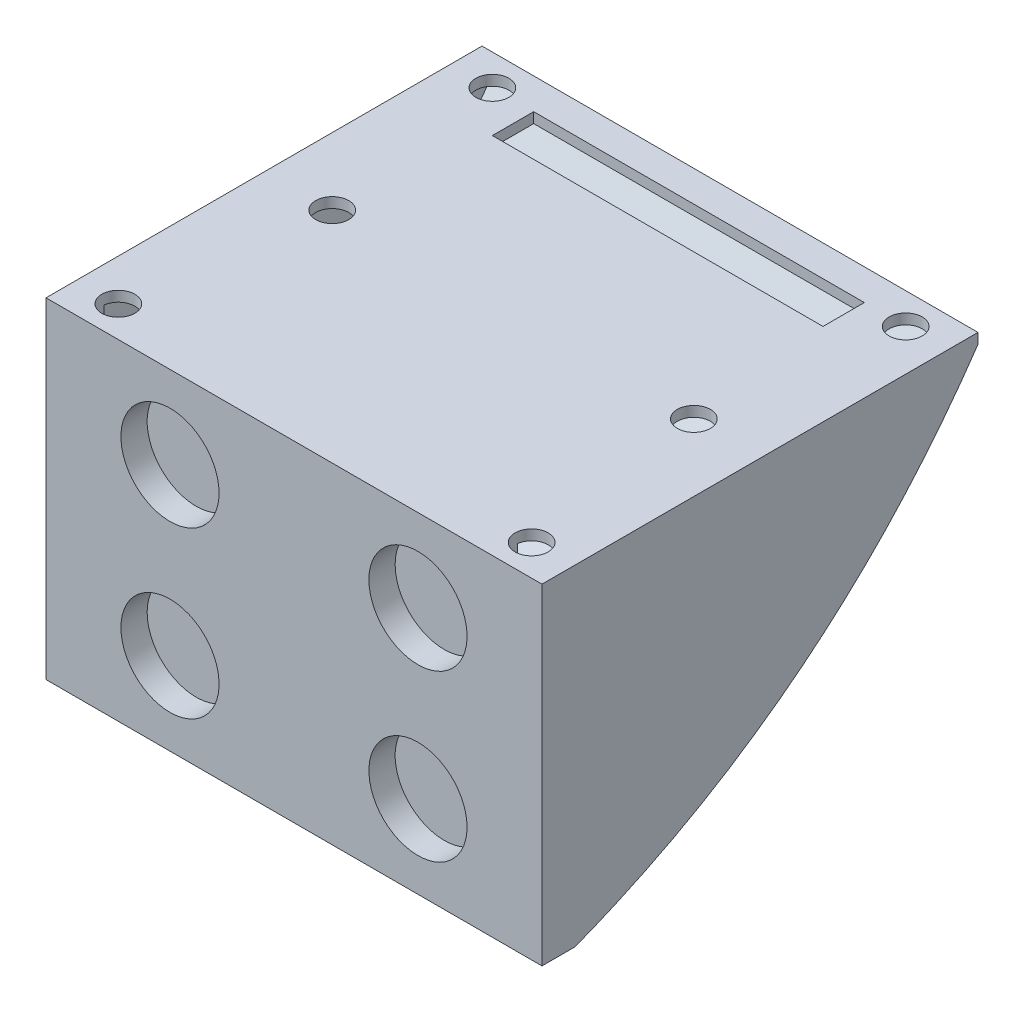
SolidWorks part; units mm, degrees
ref_plane "Alzado" through (0, 0, 0) normal (0, 0, 1) x (1, 0, 0)
ref_plane "Planta" through (0, 0, 0) normal (0, 1, 0) x (1, 0, 0)
ref_plane "Vista lateral" through (0, 0, 0) normal (1, 0, 0) x (0, 0, -1)
sketch "Croquis1" plane through (0, 0, 0) normal (0, 0, 1) x (1, 0, 0)
  line L1 (0, 32) -> (48, 32)
  line L2 (0, 32) -> (0, 0)
  line L3 (0, 0) -> (48, 0)
  line L4 (48, 32) -> (48, 0)
  dimension "D1" = 32
  dimension "D2" = 48
extrude "Saliente-Extruir1" add sketch "Croquis1" along normal blind 3.2
sketch "Croquis2" plane through (0, 0, 0) normal (0, 0, -1) x (-1, 0, 0)
  line L0 (-48, 0) -> (-48, 32) construction
  line L1 (-48, 32) -> (0, 32)
  line L2 (-48, 32) -> (-48, 31)
  line L3 (-48, 31) -> (0, 31)
  line L4 (0, 32) -> (0, 31)
  line L5 (0, 32) -> (0, 0) construction
  dimension "D1" = 1
extrude "Saliente-Extruir2" add sketch "Croquis2" along normal blind 39
sketch "Croquis3" plane through (0, 32, 0) normal (0, 1, 0) x (1, 0, 0)
  line L0 (6.5, 39) -> (6.5, 0) construction
  line L1 (0, 39) -> (48, 39) construction
  line L2 (0, 0) -> (48, 0) construction
  line L3 (41.5, 39) -> (41.5, 0) construction
  line L4 (48, 0) -> (0, 0) construction
  line L5 (24, 39) -> (24, 0) construction
  line L6 (0, 18) -> (48, 18) construction
  line L7 (0, 39) -> (0, -3.2) construction
  line L8 (48, 39) -> (48, -3.2) construction
  dimension "D1" = 35
  dimension "D2" = 17.5
  dimension "D3" = 18
hole_wizard "Taladro de margen para M31" positions "Croquis3D1" profile "Croquis4" hole size "M3" standard "ISO" end condition up to next
sketch3d "Croquis3D1"
  line L0 (6.5, 32, -39) -> (6.5, 32, 0) construction
  line L1 (0, 32, -18) -> (48, 32, -18) construction
  line L2 (41.5, 32, -39) -> (41.5, 32, 0) construction
  point P0 (6.5, 32, -18)
  point P6 (41.5, 32, -18)
sketch "Croquis4" plane through (6.5, 32, -18) normal (1, 0, 0) x (0, 0, 1)
  line L0 (0, 0) -> (0, 1)
  line L1 (0, 1) -> (1.6, 1)
  line L2 (1.6, 1) -> (1.6, 0)
  line L5 (1.6, 0) -> (0, 0)
  line L11 (0, -6.35) -> (0, 107.95) construction
  dimension "Diámetro de taladro hasta el siguiente" = 3.2
  dimension "Profundidad de taladro hasta el siguiente" = 1
sketch "Croquis5" plane through (0, 0, 0) normal (-1, 0, 0) x (0, 0, 1)
  line L0 (0, 31) -> (-39, 31)
  line L1 (0, 0) -> (0, 31)
  line L2 (0, 31) -> (-0.1248, 25.9941)
  spline S0 degree 2 poles (-39, 31) (-24.2252, 9.373) (0, 0) knots 0 0 0 1 1 1
  dimension "D1" = 20
  dimension "D2" = 20
extrude "Saliente-Extruir3" add sketch "Croquis5" against normal up to surface (48 mm away) up to face at (48, 18.4167, -15.1833)
sketch "Croquis6" plane through (0, 0, 0) normal (-1, 0, 0) x (0, 0, 1)
  line L0 (0, 31) -> (-38, 31)
  line L1 (0, 31) -> (0, 1)
  line L2 (-39, 32) -> (3.2, 32) construction
  spline S0 degree 2 poles (-38, 31) (-22.6679, 11.3023) (0, 1) knots 0 0 0 1 1 1
  dimension "D1" = 1
  dimension "D2" = 1
  dimension "D3" = 1
  dimension "D4" = 20
  dimension "D5" = 18
extrude "Cortar-Extruir1" cut sketch "Croquis6" against normal blind 46
sketch "Croquis7" plane through (0, 0, 0) normal (0, -1, 0) x (1, 0, 0)
  line L0 (0, 0) -> (0, -39) construction
  line L1 (2, 0) -> (46, 0)
  line L2 (2, 0) -> (2, -14)
  line L3 (2, -14) -> (46, -14)
  line L4 (46, 0) -> (46, -14)
  line L5 (48, -39) -> (48, 0) construction
  line L6 (0, 0) -> (48, 0) construction
  dimension "D1" = 2
  dimension "D2" = 2
  dimension "D3" = 0
  dimension "D4" = 14
extrude "Cortar-Extruir2" cut sketch "Croquis7" against normal up to next
sketch "Croquis8" plane through (0, 0, 0) normal (-1, 0, 0) x (0, 0, 1)
  line L0 (-38, 31) -> (0, 31)
  line L1 (0, 31) -> (0, 1)
  parabola Q0 (-38, 31) -> (0, 1) focus (9.8353, 52.072) apex (-20.4178, 13.3244) construction
  spline S0 degree 2 poles (-38, 31) (-22.6679, 11.3023) (0, 1) knots 0 0 0 1 1 1
  dimension "D1" = 20
extrude "Saliente-Extruir4" add sketch "Croquis8" against normal blind 2
sketch "Croquis9" plane through (0, 32, 0) normal (0, 1, 0) x (1, 0, 0)
  line L1 (8, 32) -> (40, 32)
  line L2 (8, 32) -> (8, 36)
  line L3 (8, 36) -> (40, 36)
  line L4 (40, 32) -> (40, 36)
  line L5 (0, 39) -> (0, -3.2) construction
  line L6 (48, 39) -> (48, -3.2) construction
  line L8 (0, 39) -> (48, 39) construction
  dimension "D1" = 4
  dimension "D2" = 8
  dimension "D3" = 8
  dimension "D4" = 3
extrude "Cortar-Extruir3" cut sketch "Croquis9" against normal up to next
sketch "Croquis10" plane through (0, 0, 3.2) normal (0, 0, 1) x (1, 0, 0)
  line L0 (0, 16) -> (48, 16) construction
  line L1 (0, 32) -> (0, 0) construction
  line L2 (48, 0) -> (48, 32) construction
  line L3 (24, 32) -> (24, 0) construction
  line L4 (48, 32) -> (0, 32) construction
  line L5 (0, 0) -> (48, 0) construction
  circle A0 centre (12, 24) radius 4.75
  circle A1 centre (36, 24) radius 4.75
  circle A2 centre (36, 8) radius 4.75
  circle A3 centre (12, 8) radius 4.75
  dimension "D1" = 9.5
  dimension "D2" = 12
  dimension "D3" = 8
extrude "Cortar-Extruir4" cut sketch "Croquis10" against normal blind 2.54
sketch "Croquis11" plane through (0, 32, 0) normal (0, 1, 0) x (1, 0, 0)
  line L0 (0, -0.2) -> (48, -0.2) construction
  line L1 (0, -3.2) -> (0, 39) construction
  line L2 (48, -3.2) -> (48, 39) construction
  line L3 (4, 39) -> (4, -3.2) construction
  line L4 (0, 39) -> (48, 39) construction
  line L5 (48, -3.2) -> (0, -3.2) construction
  line L6 (0, 36) -> (48, 36) construction
  line L7 (44, 39) -> (44, -3.2) construction
  dimension "D1" = 3
  dimension "D2" = 4
  dimension "D3" = 4
  dimension "D4" = 3
hole_wizard "Taladro de margen para M32" positions "Croquis3D2" profile "Croquis12" hole size "M3" standard "ISO"
sketch3d "Croquis3D2"
  line L0 (4, 32, -39) -> (4, 32, 3.2) construction
  line L1 (0, 32, -36) -> (48, 32, -36) construction
  line L2 (0, 32, 0.2) -> (48, 32, 0.2) construction
  line L3 (44, 32, -39) -> (44, 32, 3.2) construction
  point P0 (4, 32, -36)
  point P6 (4, 32, 0.2)
  point P10 (44, 32, 0.2)
  point P14 (44, 32, -36)
sketch "Croquis12" plane through (4, 32, -36) normal (1, 0, 0) x (0, 0, 1)
  line L0 (0, 0) -> (0, 1)
  line L1 (0, 1) -> (1.6, 1)
  line L2 (1.6, 1) -> (1.6, 0)
  line L5 (1.6, 0) -> (0, 0)
  line L11 (0, -6.35) -> (0, 107.95) construction
  dimension "Diámetro de taladro hasta el siguiente" = 3.2
  dimension "Profundidad de taladro hasta el siguiente" = 1
